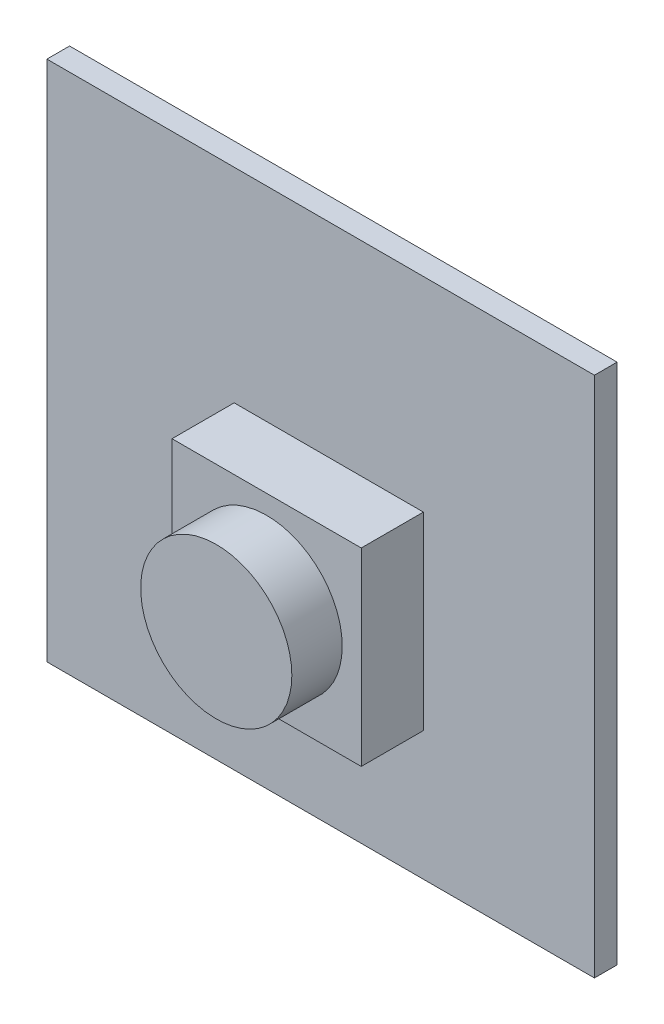
SolidWorks part; units mm, degrees
ref_plane "Front Plane" through (0, 0, 0) normal (0, 0, 1) x (1, 0, 0)
ref_plane "Top Plane" through (0, 0, 0) normal (0, 1, 0) x (1, 0, 0)
ref_plane "Right Plane" through (0, 0, 0) normal (1, 0, 0) x (0, 0, -1)
sketch "Sketch1" plane through (0, 0, 0) normal (0, 0, 1) x (1, 0, 0)
  line L1 (-12.4206, 11.8427) -> (12.4206, 11.8427)
  line L2 (-12.4206, 11.8427) -> (-12.4206, -11.8428)
  line L3 (-12.4206, -11.8428) -> (12.4206, -11.8428)
  line L4 (12.4206, 11.8427) -> (12.4206, -11.8428)
  line L5 (-12.4206, 11.8427) -> (12.4206, -11.8428) construction
  line L6 (-12.4206, -11.8428) -> (12.4206, 11.8427) construction
  point P0 (0, 0)
extrude "Boss-Extrude1" add sketch "Sketch1" along normal blind 1.0287
sketch "Sketch2" plane through (0, 0, 1.0287) normal (0, 0, 1) x (1, 0, 0)
  line L0 (-12.4206, -11.8428) -> (12.4206, -11.8428) construction
  line L1 (-3.9243, 2.5845) -> (4.6609, 2.5845)
  line L2 (-3.9243, 2.5845) -> (-3.9243, -6.0008)
  line L3 (-3.9243, -6.0008) -> (4.6609, -6.0008)
  line L4 (4.6609, 2.5845) -> (4.6609, -6.0008)
  line L5 (-3.9243, 2.5845) -> (4.6609, -6.0008) construction
  line L6 (-3.9243, -6.0008) -> (4.6609, 2.5845) construction
  line L7 (12.4206, -11.8428) -> (12.4206, 11.8427) construction
  point P0 (0.3683, -1.7082)
  dimension "D1" = 8.5852
  dimension "D2" = 8.5852
  dimension "D3" = 5.842
  dimension "D4" = 7.7597
extrude "Boss-Extrude2" add sketch "Sketch2" along normal blind 2.8194
sketch "Sketch3" plane through (0, 0, 3.8481) normal (0, 0, 1) x (1, 0, 0)
  line L0 (-3.9243, 2.5845) -> (-3.9243, -6.0008) construction
  line L1 (-3.9243, -6.0008) -> (4.6609, -6.0008) construction
  circle A0 centre (0.3683, -1.7082) radius 3.429
  dimension "D1" = 4.2926
  dimension "D2" = 4.2926
extrude "Boss-Extrude3" add sketch "Sketch3" along normal blind 2.286
